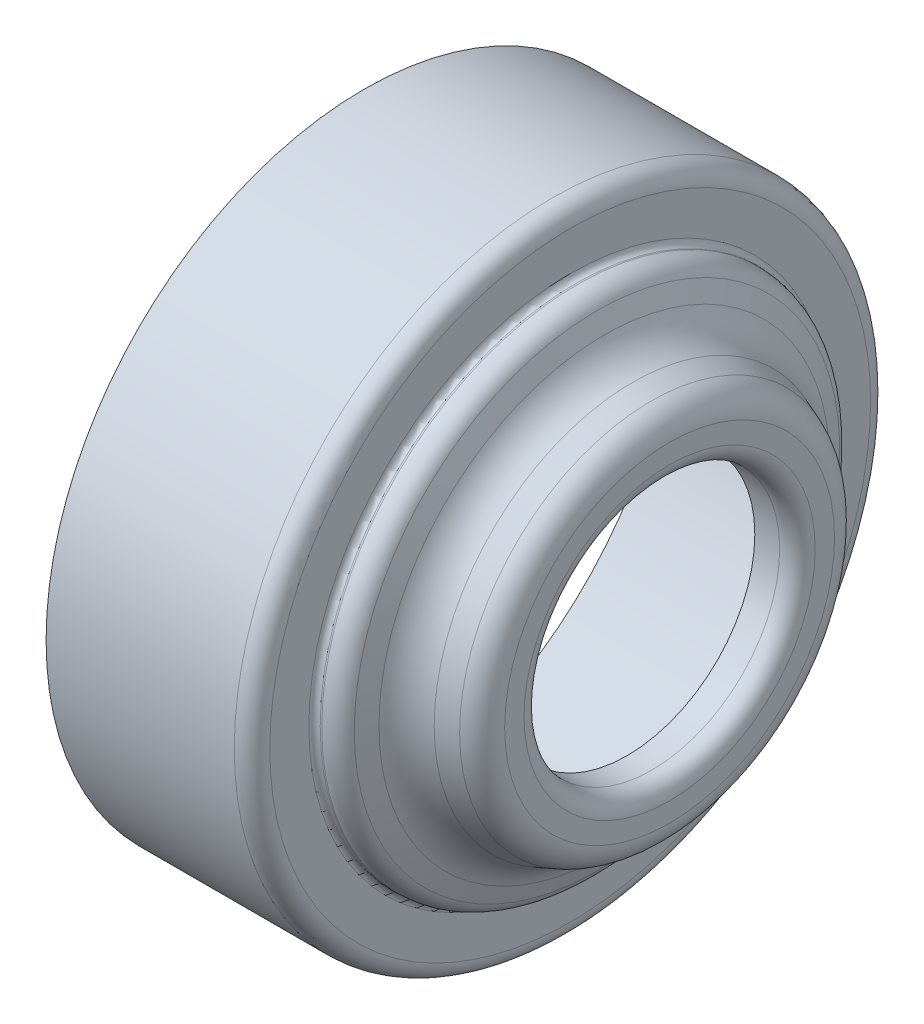
SolidWorks part; units mm, degrees
ref_plane "前视基准面" through (0, 0, 0) normal (0, 0, 1) x (1, 0, 0)
ref_plane "上视基准面" through (0, 0, 0) normal (0, 1, 0) x (1, 0, 0)
ref_plane "右视基准面" through (0, 0, 0) normal (1, 0, 0) x (0, 0, -1)
sketch "草图1" plane through (0, 0, 0) normal (0, 0, 1) x (1, 0, 0)
  line L0 (-28.9725, 0) -> (27.6414, 0) construction
  line L1 (0, 33.7643) -> (0, -38.2898) construction
  line L2 (-14.5, 22.4) -> (-1.25, 22.4)
  line L3 (0, 21.15) -> (0, 18.4)
  line L4 (0.4, 18) -> (0.5109, 18)
  line L5 (1.8896, 17.0909) -> (2.4113, 15.8737)
  line L6 (4.3994, 13.9752) -> (5.7022, 13.4867)
  line L7 (7, 11.614) -> (7, 10.25)
  line L8 (5.75, 9) -> (4, 9)
  line L9 (-14.5, 22) -> (-1.25, 22)
  line L10 (-0.4, 21.15) -> (-0.4, 18.4)
  line L11 (0.4, 17.6) -> (0.5109, 17.6)
  line L12 (1.522, 16.9333) -> (2.0436, 15.7161)
  line L13 (4.2589, 13.6007) -> (5.5618, 13.1121)
  line L14 (6.6, 11.614) -> (6.6, 10.25)
  line L15 (5.75, 9.4) -> (4, 9.4)
  line L16 (-14.5, 22.4) -> (-14.5, 22)
  line L17 (4, 9.4) -> (4, 9)
  arc A0 (0, 21.15) -> (-1.25, 22.4) centre (-1.25, 21.15) ccw
  arc A1 (0, 18.4) -> (0.4, 18) centre (0.4, 18.4) ccw
  arc A2 (1.8896, 17.0909) -> (0.5109, 18) centre (0.5109, 16.5) ccw
  arc A3 (2.4113, 15.8737) -> (4.3994, 13.9752) centre (5.6283, 17.2524) ccw
  arc A4 (7, 11.614) -> (5.7022, 13.4867) centre (5, 11.614) ccw
  arc A5 (7, 10.25) -> (5.75, 9) centre (5.75, 10.25) cw
  arc A6 (-0.4, 21.15) -> (-1.25, 22) centre (-1.25, 21.15) ccw
  arc A7 (-0.4, 18.4) -> (0.4, 17.6) centre (0.4, 18.4) ccw
  arc A8 (1.522, 16.9333) -> (0.5109, 17.6) centre (0.5109, 16.5) ccw
  arc A9 (2.0436, 15.7161) -> (4.2589, 13.6007) centre (5.6283, 17.2524) ccw
  arc A10 (6.6, 11.614) -> (5.5618, 13.1121) centre (5, 11.614) ccw
  arc A11 (6.6, 10.25) -> (5.75, 9.4) centre (5.75, 10.25) cw
  point P15 (0, 22.4)
  point P18 (0, 18)
  point P21 (1.5, 18)
  point P24 (3, 14.5)
  point P27 (7, 13)
  point P30 (7, 9)
  dimension "D11" = 1.25
  dimension "D12" = 0.4
  dimension "D13" = 1.5
  dimension "D14" = 3.5
  dimension "D15" = 2
  dimension "D16" = 1.25
  dimension "D1" = 44.8
  dimension "D2" = 18
  dimension "D3" = 36
  dimension "D4" = 29
  dimension "D5" = 1.5
  dimension "D6" = 14.5
  dimension "D7" = 3
  dimension "D8" = 7
  dimension "D9" = 26
  dimension "D10" = 3
  dimension "D17" = 0.4
revolve "旋转1" add sketch "草图1" angle 360 about L0
